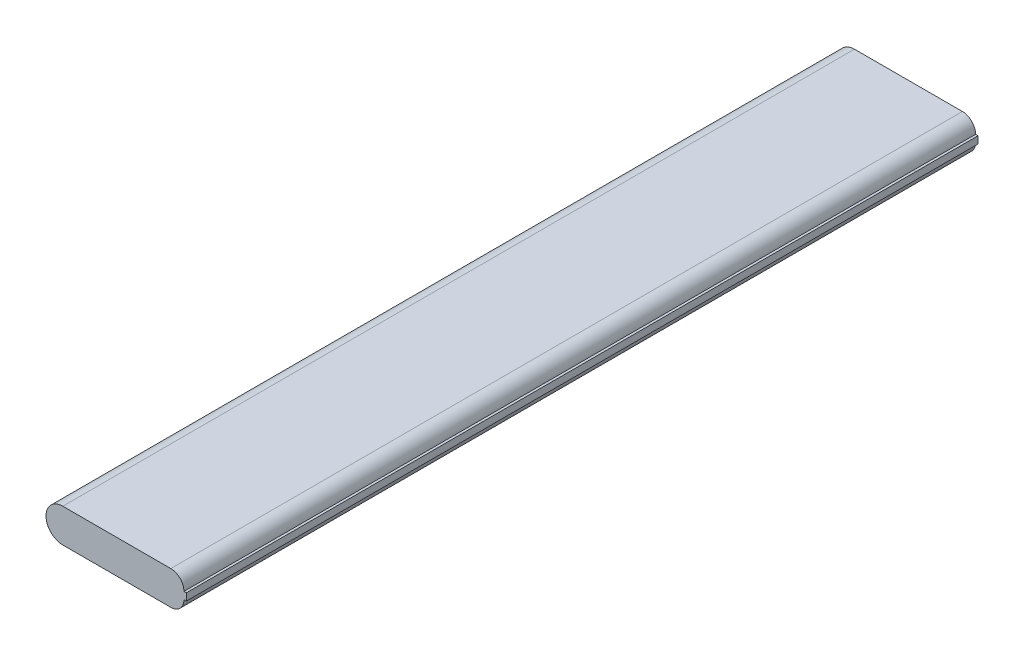
SolidWorks part; units mm, degrees
material "1060 Alloy"
ref_plane "Front Plane" through (0, 0, 0) normal (0, 0, 1) x (1, 0, 0)
ref_plane "Top Plane" through (0, 0, 0) normal (0, 1, 0) x (1, 0, 0)
ref_plane "Right Plane" through (0, 0, 0) normal (1, 0, 0) x (0, 0, -1)
sketch "Sketch1" plane through (0, 0, 0) normal (0, 0, 1) x (1, 0, 0)
  line L0 (0, 0) -> (14.5, 0) construction
  line L1 (-11.25, 3.5) -> (11.25, 3.5)
  line L2 (14, 0.75) -> (14.5, 0.75)
  line L3 (14.5, 0.75) -> (14.5, -0.75)
  line L4 (14, -0.75) -> (14.5, -0.75)
  line L5 (-11.25, -3.5) -> (11.25, -3.5)
  arc A0 (-11.25, 3.5) -> (-11.25, -3.5) centre (-11.25, 0) ccw
  arc A1 (11.25, 3.5) -> (14, 0.75) centre (11.25, 0.75) cw
  arc A2 (11.25, -3.5) -> (14, -0.75) centre (11.25, -0.75) ccw
  point P6 (0, 3.5)
  dimension "D1" = 22.5
  dimension "D2" = 7
  dimension "D3" = 1.5
  dimension "D4" = 0.5
extrude "Boss-Extrude1" add sketch "Sketch1" along normal mid plane 165
